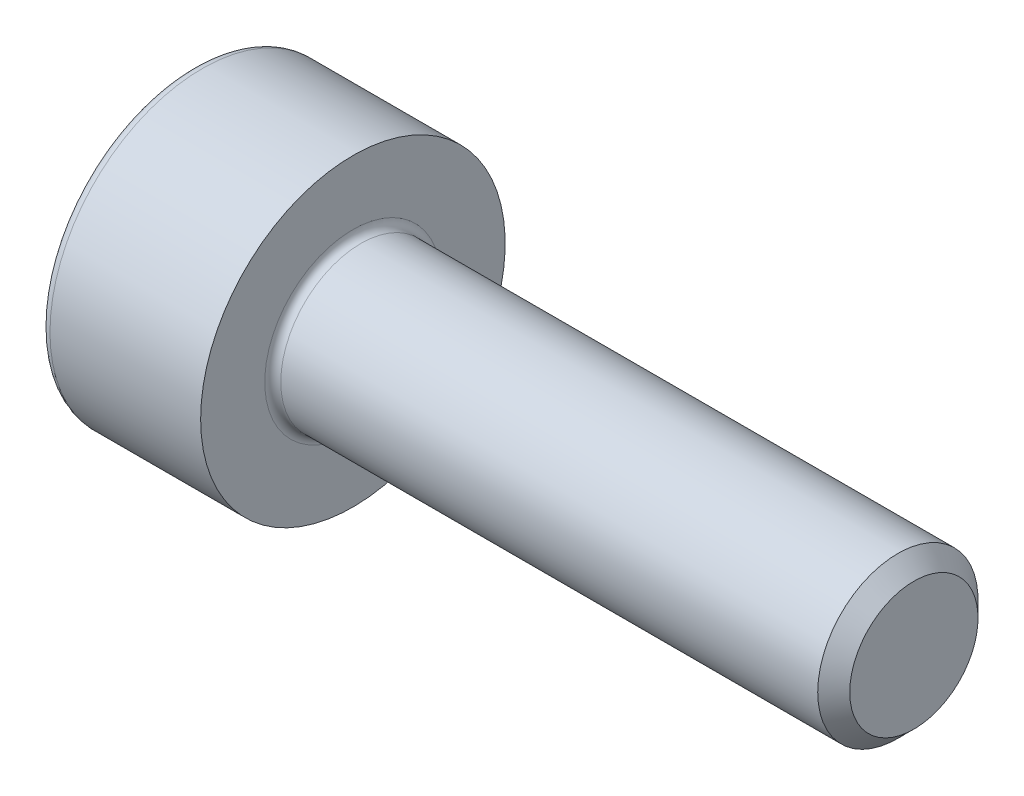
SolidWorks part; units mm, degrees
ref_plane "Front Plane" through (0, 0, 0) normal (0, 0, 1) x (1, 0, 0)
ref_plane "Top Plane" through (0, 0, 0) normal (0, 1, 0) x (1, 0, 0)
ref_plane "Right Plane" through (0, 0, 0) normal (1, 0, 0) x (0, 0, -1)
sketch "Sketch1" plane through (0, 0, 0) normal (0, 0, 1) x (1, 0, 0)
  line L0 (0, 0) -> (0, 1.9)
  line L1 (0, 1.9) -> (2, 1.9)
  line L2 (2, 1.9) -> (2, 0)
  line L3 (0, 0) -> (4.2799, 0) construction
  line L4 (2, 0) -> (9, 0)
  line L5 (9, 0) -> (9, 1)
  line L6 (9, 1) -> (2, 1)
  dimension "D1" = 7
revolve "Revolve1" add sketch "Sketch1" angle 360 about L3
fillet "Fillet1" radius 0.1 1 edges at (2, 0, 1)
fillet "Fillet2" radius 0.12 1 edges at (0, 0, 1.9)
chamfer "Chamfer1" distance 0.2 angle 45 1 edges at (9, 0, 1)
sketch "Sketch2" plane through (0, 0, 0) normal (-1, 0, 0) x (0, 0, 1)
  line L1 (0, 0.866) -> (-0.75, 0.433)
  line L2 (-0.75, 0.433) -> (-0.75, -0.433)
  line L3 (-0.75, -0.433) -> (0, -0.866)
  line L4 (0, -0.866) -> (0.75, -0.433)
  line L5 (0.75, -0.433) -> (0.75, 0.433)
  line L6 (0.75, 0.433) -> (0, 0.866)
  circle A0 centre (0, 0) radius 0.75 construction
extrude "Extrude1" cut sketch "Sketch2" against normal blind 1
